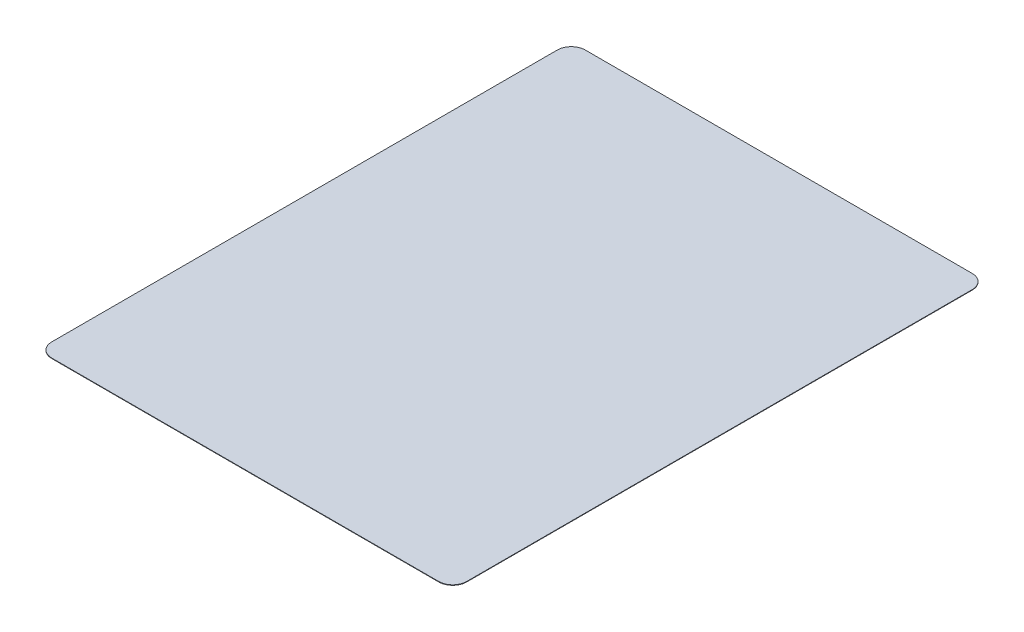
SolidWorks part; units mm, degrees
ref_plane "Front Plane" through (0, 0, 0) normal (0, 0, 1) x (1, 0, 0)
ref_plane "Top Plane" through (0, 0, 0) normal (0, 1, 0) x (1, 0, 0)
ref_plane "Right Plane" through (0, 0, 0) normal (1, 0, 0) x (0, 0, -1)
sketch "Sketch1" plane through (0, 0, 0) normal (0, 1, 0) x (1, 0, 0)
  line L1 (44.45, -57.15) -> (-44.45, -57.15)
  line L2 (44.45, -57.15) -> (44.45, 57.15)
  line L3 (44.45, 57.15) -> (-44.45, 57.15)
  line L4 (-44.45, -57.15) -> (-44.45, 57.15)
  line L5 (44.45, -57.15) -> (-44.45, 57.15) construction
  line L6 (44.45, 57.15) -> (-44.45, -57.15) construction
  point P0 (0, 0)
  dimension "D1" = 88.9
  dimension "D2" = 114.3
extrude "Boss-Extrude1" add sketch "Sketch1" along normal blind 0.1
fillet "Fillet1" radius 3 4 edges at (-44.45, 0.05, 57.15) (-44.45, 0.05, -57.15) (44.45, 0.05, -57.15) (44.45, 0.05, 57.15)
